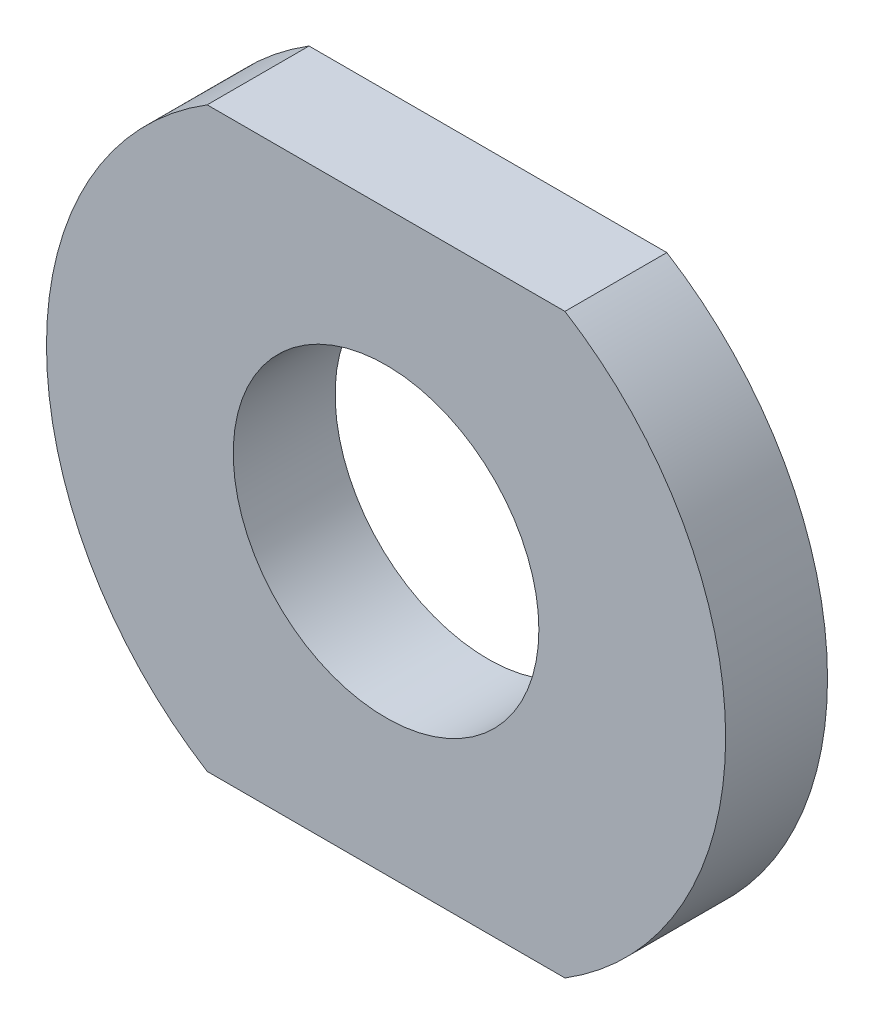
SolidWorks part; units mm, degrees
ref_plane "前视基准面" through (0, 0, 0) normal (0, 0, 1) x (1, 0, 0)
ref_plane "上视基准面" through (0, 0, 0) normal (0, 1, 0) x (1, 0, 0)
ref_plane "右视基准面" through (0, 0, 0) normal (1, 0, 0) x (0, 0, -1)
sketch "草图1" plane through (0, 0, 0) normal (0, 0, 1) x (1, 0, 0)
  line L0 (0, 0) -> (16.7135, 0) construction
  line L1 (-5.2678, 8.5) -> (5.2678, 8.5)
  line L3 (-5.2678, -8.5) -> (5.2678, -8.5)
  circle A0 centre (0, 0) radius 4.5
  arc A1 (-5.2678, 8.5) -> (-5.2678, -8.5) centre (0, 0) ccw
  arc A2 (5.2678, -8.5) -> (5.2678, 8.5) centre (0, 0) ccw
  dimension "D1" = 9
  dimension "D2" = 20
  dimension "D3" = 17
extrude "凸台-拉伸1" add sketch "草图1" along normal blind 3
cosmetic thread "装饰螺纹线3" parameters "D2"=10
